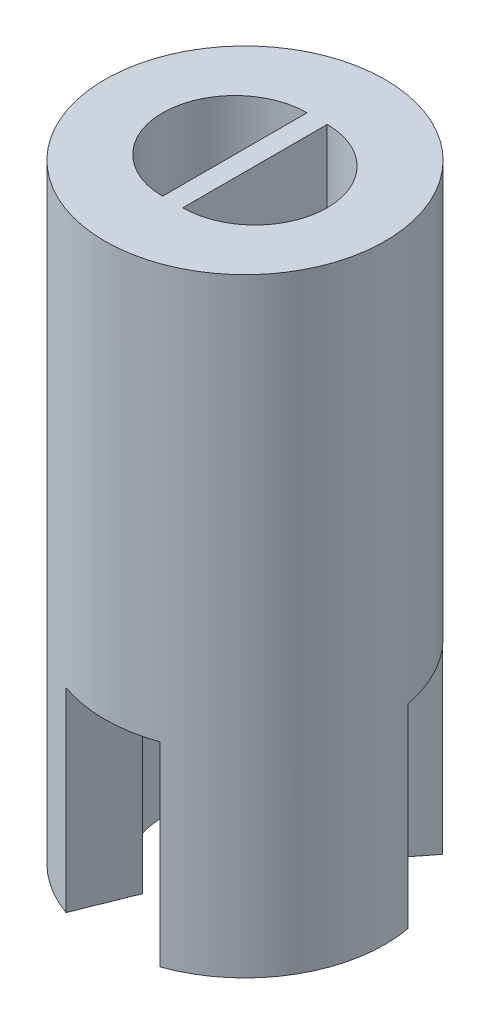
SolidWorks part; units mm, degrees
ref_plane "Front Plane" through (0, 0, 0) normal (0, 0, 1) x (1, 0, 0)
ref_plane "Top Plane" through (0, 0, 0) normal (0, 1, 0) x (1, 0, 0)
ref_plane "Right Plane" through (0, 0, 0) normal (1, 0, 0) x (0, 0, -1)
sketch "Sketch1" plane through (0, 0, 0) normal (0, 1, 0) x (1, 0, 0)
  circle A0 centre (0, 0) radius 5.75
  dimension "D1" = 11.5
extrude "Boss-Extrude1" add sketch "Sketch1" along normal blind 25
sketch "Sketch2" plane through (0, 0, 0) normal (0, 1, 0) x (1, 0, 0)
  circle A0 centre (0, 0) radius 3.3415
extrude "Cut-Extrude1" cut sketch "Sketch2" along normal blind 15
sketch "Sketch5" plane through (0, 0, 0) normal (0, 1, 0) x (1, 0, 0)
  line L0 (-1.0357, -3.177) -> (-1.9334, -5.4152)
  line L1 (0, -7.0066) -> (0, 0) construction
  line L2 (1.0357, -3.177) -> (1.9334, -5.4152)
  circle A0 centre (0, 0) radius 3.3415 construction
  circle A1 centre (0, 0) radius 5.75 construction
  arc A2 (-1.9334, -5.4152) -> (1.9334, -5.4152) centre (0, 0) ccw
  arc A3 (-1.0357, -3.177) -> (1.0357, -3.177) centre (0, 0) ccw
extrude "Cut-Extrude2" cut sketch "Sketch5" along normal blind 8
pattern_circular "CirPattern1" count 3 over 360 about axis through (0, 0, 0) along (0, 1, 0) of "Cut-Extrude2"
sketch "Sketch6" plane through (0, 25, 0) normal (0, 1, 0) x (1, 0, 0)
  line L4 (0.41, 2.9647) -> (0.41, -2.9647)
  line L5 (-0.4164, 2.9656) -> (-0.4164, -2.9656)
  arc A3 (0.41, 2.9647) -> (0.41, -2.9647) centre (0.41, 0) cw
  arc A4 (-0.4164, 2.9656) -> (-0.4164, -2.9656) centre (-0.4164, 0) ccw
  dimension "D2" = 0.41
extrude "Cut-Extrude3" cut sketch "Sketch6" against normal blind 8
sketch "Sketch7" plane through (0, 15, 0) normal (0, -1, 0) x (1, 0, 0)
  circle A0 centre (0, 0) radius 0.9
  dimension "D1" = 1.8
extrude "Cut-Extrude4" cut sketch "Sketch7" against normal blind 0.1
